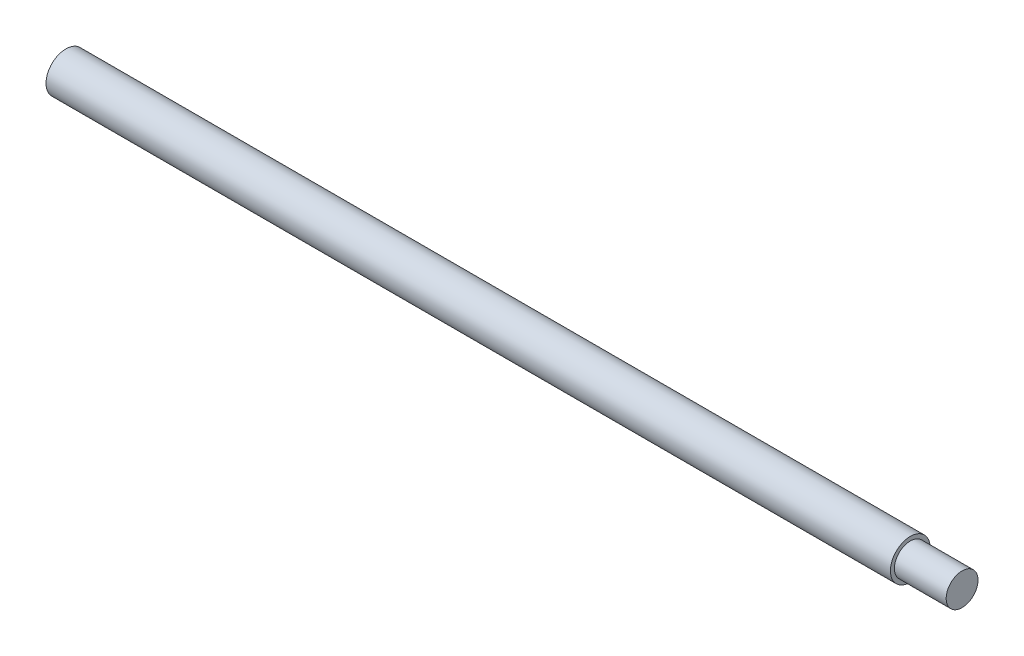
SolidWorks part; units mm, degrees
ref_plane "Front Plane" through (0, 0, 0) normal (0, 0, 1) x (1, 0, 0)
ref_plane "Top Plane" through (0, 0, 0) normal (0, 1, 0) x (1, 0, 0)
ref_plane "Right Plane" through (0, 0, 0) normal (1, 0, 0) x (0, 0, -1)
sketch "Sketch1" plane through (0, 0, 0) normal (0, 0, 1) x (1, 0, 0)
  line L0 (0, 0) -> (112.5, 0) construction
  line L1 (0, 0) -> (0, 2.5)
  line L2 (0, 2.5) -> (106, 2.5)
  line L3 (106, 2.5) -> (106, 2)
  line L4 (106, 2) -> (112.5, 2)
  line L5 (112.5, 2) -> (112.5, 0)
  line L6 (0, 0) -> (112.5, 0)
  dimension "D1" = 2.5
  dimension "D2" = 6.5
  dimension "D3" = 106
  dimension "D4" = 2
revolve "Revolve1" add sketch "Sketch1" angle 360 about L0
sketch "Sketch2" plane through (0, 0, 0) normal (-1, 0, 0) x (0, 0, 1)
  circle A0 centre (0, 0) radius 2
  dimension "D1" = 4
extrude "Cut-Extrude1" cut sketch "Sketch2" against normal blind 14
